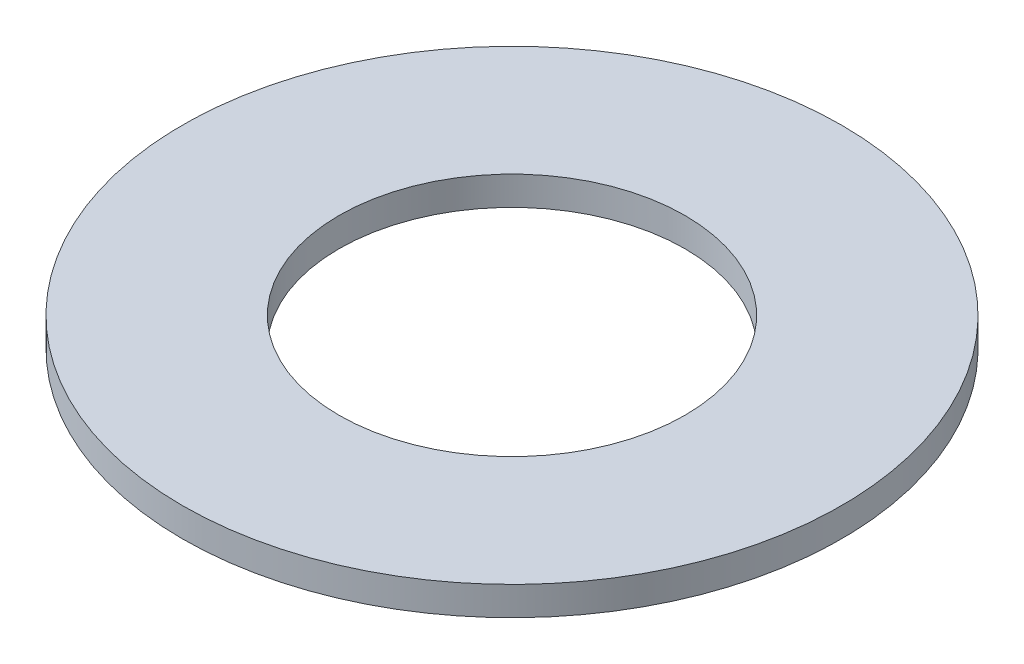
SolidWorks part; units mm, degrees
material "Acier allié"
ref_plane "Plan de face" through (0, 0, 0) normal (0, 0, 1) x (1, 0, 0)
ref_plane "Plan de dessus" through (0, 0, 0) normal (0, 1, 0) x (1, 0, 0)
ref_plane "Plan de droite" through (0, 0, 0) normal (1, 0, 0) x (0, 0, -1)
sketch "Esquisse1" plane through (0, 0, 0) normal (0, 1, 0) x (1, 0, 0)
  circle A0 centre (0, 0) radius 8
  circle A1 centre (0, 0) radius 4.2
  dimension "D1" = 16
  dimension "D2" = 8.4
extrude "Boss.-Extru.1" add sketch "Esquisse1" along normal blind 0.7
